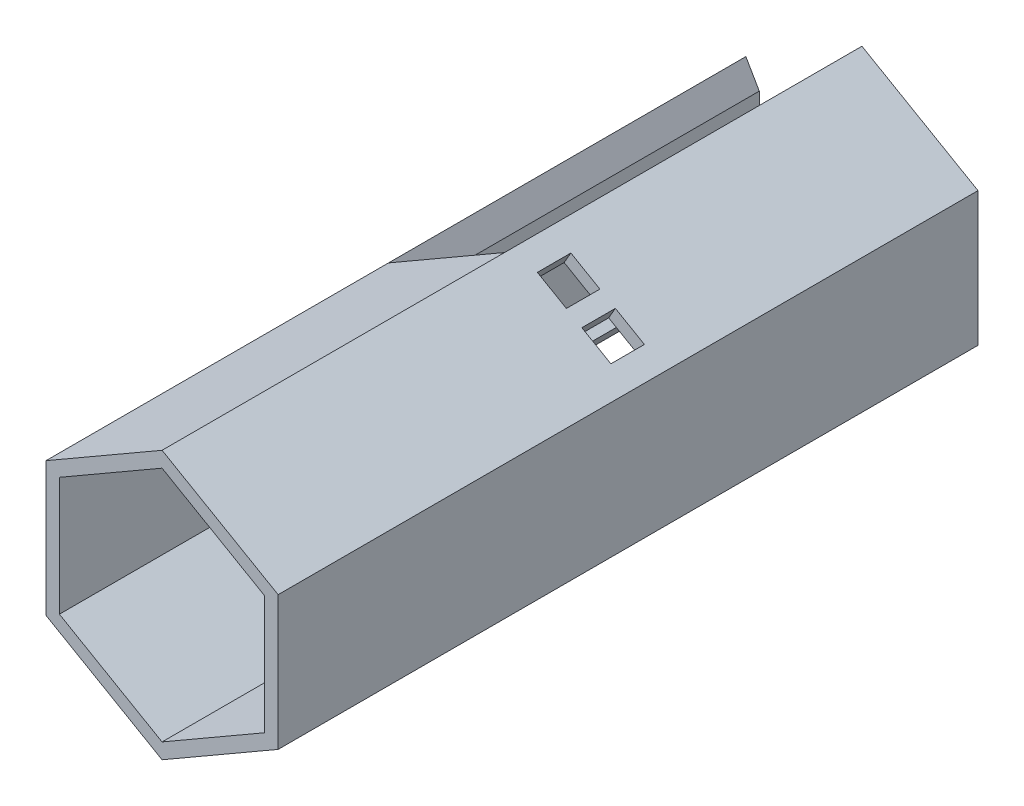
SolidWorks part; units mm, degrees
ref_plane "Front Plane" through (0, 0, 0) normal (0, 0, 1) x (1, 0, 0)
ref_plane "Top Plane" through (0, 0, 0) normal (0, 1, 0) x (1, 0, 0)
ref_plane "Right Plane" through (0, 0, 0) normal (1, 0, 0) x (0, 0, -1)
sketch "Sketch1" plane through (0, 0, 0) normal (0, 0, 1) x (1, 0, 0)
  line L5 (-137.8846, 79.6077) -> (-137.8846, -79.6077)
  line L6 (0, 180) -> (-155.8846, 90)
  line L10 (-155.8846, 90) -> (-155.8846, -90)
  line L11 (-155.8846, -90) -> (0, -180)
  line L12 (0, -180) -> (155.8846, -90)
  line L13 (155.8846, -90) -> (155.8846, 90)
  line L14 (155.8846, 90) -> (0, 180)
  line L15 (-137.8846, -79.6077) -> (0, -159.2154)
  line L16 (0, -159.2154) -> (137.8846, -79.6077)
  line L17 (137.8846, -79.6077) -> (137.8846, 79.6077)
  line L18 (137.8846, 79.6077) -> (0, 159.2154)
  line L19 (0, 159.2154) -> (-137.8846, 79.6077)
  circle A0 centre (0, 0) radius 155.8846 construction
  dimension "D1" = 180
  dimension "D2" = 18
extrude "Boss-Extrude2" add sketch "Sketch1" along normal blind 940
sketch "Sketch3" plane through (155.8846, 0, 0) normal (1, 0, 0) x (0, 0, -1)
  line L0 (-480, 90) -> (-480, -90) construction
  line L1 (-940, -90) -> (0, -90) construction
  line L2 (-477, 90) -> (-477, -90) construction
  line L3 (-477, 0) -> (0, 0) construction
  line L4 (-464.5, 12) -> (-419.5, 12)
  line L5 (-464.5, -57) -> (-419.5, -57)
  line L6 (-464.5, -57) -> (-464.5, -12)
  line L7 (-464.5, -12) -> (-419.5, -12)
  line L8 (-419.5, -57) -> (-419.5, -12)
  line L9 (-419.5, 57) -> (-419.5, 12)
  line L10 (-464.5, 57) -> (-419.5, 57)
  line L11 (-464.5, 57) -> (-464.5, 12)
  line L16 (-940, 90) -> (0, 90) construction
  line L17 (0, -90) -> (0, 90) construction
  dimension "D2" = 12
  dimension "D3" = 45
  dimension "D4" = 45
  dimension "D5" = 12.5
  dimension "D6" = 419.5
  dimension "D1" = 3
sketch "Sketch4" plane through (77.9423, -135, 0) normal (0.5, -0.866, 0) x (0.866, 0.5, 0)
  line L2 (90, 480) -> (-90, 480) construction
  line L3 (90, 940) -> (90, 0) construction
  line L4 (-90, 940) -> (-90, 0) construction
  line L5 (-90, 0) -> (90, 0) construction
  line L6 (90, 477) -> (-90, 477) construction
  line L7 (0, 480) -> (0, 0) construction
  line L9 (-22.5, 464.5) -> (22.5, 464.5)
  line L10 (-22.5, 464.5) -> (-22.5, 419.5)
  line L11 (-22.5, 419.5) -> (22.5, 419.5)
  line L12 (22.5, 464.5) -> (22.5, 419.5)
  dimension "D1" = 480
  dimension "D3" = 45
  dimension "D4" = 45
  dimension "D5" = 12.5
  dimension "D2" = 3
sketch "Sketch5" plane through (-77.9423, -135, 0) normal (-0.5, -0.866, 0) x (0.866, -0.5, 0)
  line L0 (90, 480) -> (-90, 480) construction
  line L1 (90, 940) -> (90, 0) construction
  line L2 (-90, 940) -> (-90, 0) construction
  line L3 (-90, 0) -> (90, 0) construction
  line L4 (90, 477) -> (-90, 477) construction
  line L5 (0, 477) -> (0, 0) construction
  line L6 (57, 419.5) -> (12, 419.5)
  line L7 (-57, 464.5) -> (-12, 464.5)
  line L8 (-57, 464.5) -> (-57, 419.5)
  line L9 (-57, 419.5) -> (-12, 419.5)
  line L10 (-12, 464.5) -> (-12, 419.5)
  line L11 (12, 464.5) -> (12, 419.5)
  line L12 (57, 464.5) -> (12, 464.5)
  line L13 (57, 464.5) -> (57, 419.5)
  line L15 (-20, 280) -> (20, 280)
  line L16 (-50, 250) -> (-50, 0)
  line L17 (-50, 0) -> (50, 0)
  line L18 (50, 250) -> (50, 0)
  arc A0 (50, 250) -> (20, 280) centre (20, 250) ccw
  arc A1 (-50, 250) -> (-20, 280) centre (-20, 250) cw
  point P26 (50, 280)
  point P29 (-50, 280)
  dimension "D9" = 30
  dimension "D1" = 480
  dimension "D3" = 12
  dimension "D4" = 12.5
  dimension "D5" = 45
  dimension "D6" = 45
  dimension "D7" = 100
  dimension "D8" = 280
  dimension "D2" = 3
extrude "Cut-Extrude3" cut sketch "Sketch4" against normal up to next
extrude "Cut-Extrude4" cut sketch "Sketch5" against normal up to next
sketch "Sketch7" plane through (-77.9423, 135, 0) normal (-0.5, 0.866, 0) x (0.866, 0.5, 0)
  line L0 (-90, -940) -> (-90, 0) construction
  line L1 (90, 0) -> (-90, 0)
  line L2 (90, 0) -> (90, -480)
  line L3 (90, -480) -> (-90, -480)
  line L4 (-90, 0) -> (-90, -480)
  dimension "D1" = 480
extrude "Cut-Extrude6" cut sketch "Sketch7" against normal up to next
sketch "Sketch9" plane through (77.9423, 135, 0) normal (0.5, 0.866, 0) x (0.866, -0.5, 0)
  line L0 (0, 0) -> (0, -625) construction
  line L1 (90, 0) -> (-90, 0) construction
  line L2 (-57, -464.5) -> (-57, -419.5)
  line L3 (57, -464.5) -> (12, -464.5)
  line L4 (57, -464.5) -> (57, -419.5)
  line L5 (57, -419.5) -> (12, -419.5)
  line L6 (12, -464.5) -> (12, -419.5)
  line L7 (-57, -419.5) -> (-12, -419.5)
  line L8 (-12, -464.5) -> (-12, -419.5)
  line L9 (-57, -464.5) -> (-12, -464.5)
  dimension "D1" = 45
  dimension "D2" = 45
  dimension "D3" = 419.5
  dimension "D4" = 12
extrude "Cut-Extrude7" cut sketch "Sketch9" against normal up to surface (18 mm away) up to face at (51.9615, 129.2154, 473.3333)
